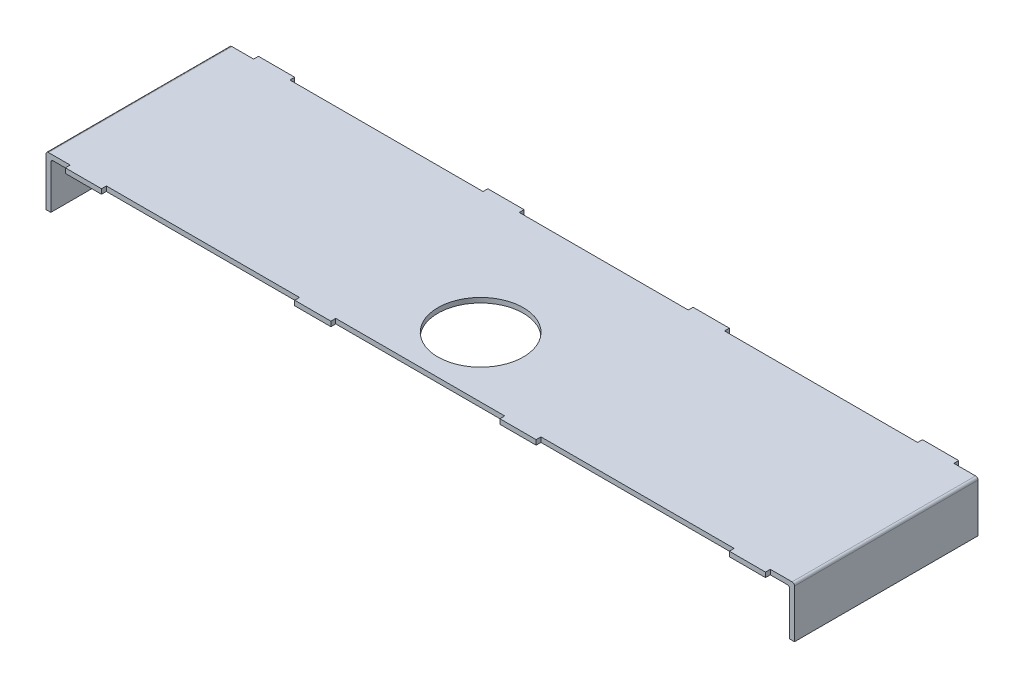
SolidWorks part; units mm, degrees
material "Hexcel AS4C (3000 丝)"
ref_plane "前视基准面" through (0, 0, 0) normal (0, 0, 1) x (1, 0, 0)
ref_plane "上视基准面" through (0, 0, 0) normal (0, 1, 0) x (1, 0, 0)
ref_plane "右视基准面" through (0, 0, 0) normal (1, 0, 0) x (0, 0, -1)
sketch "草图1" plane through (0, 0, 0) normal (0, 1, 0) x (1, 0, 0)
  line L0 (0, -25) -> (0, 25) construction
  line L1 (-155, -38) -> (-145, -38)
  line L2 (-155, -38) -> (-155, 38)
  line L3 (-155, 38) -> (-145, 38)
  line L4 (155, -38) -> (155, 38)
  line L5 (-155, -38) -> (155, 38) construction
  line L6 (-155, 38) -> (155, -38) construction
  line L7 (155, 0) -> (-155, 0) construction
  line L8 (-130, 38) -> (-50, 38)
  line L9 (-35, 38) -> (35, 38)
  line L10 (-145, 38) -> (-145, 40)
  line L11 (-145, 40) -> (-130, 40)
  line L12 (-130, 38) -> (-130, 40)
  line L13 (-145, 38) -> (-130, 40) construction
  line L14 (-145, 40) -> (-130, 38) construction
  line L15 (-50, 40) -> (-35, 40)
  line L16 (-50, 40) -> (-50, 38)
  line L17 (50, 40) -> (50, 38)
  line L18 (-35, 40) -> (-35, 38)
  line L19 (-50, 40) -> (-35, 38) construction
  line L20 (-50, 38) -> (-35, 40) construction
  line L21 (35, 40) -> (35, 38)
  line L22 (50, 40) -> (35, 40)
  line L23 (130, 38) -> (130, 40)
  line L24 (145, 38) -> (145, 40)
  line L25 (145, 40) -> (130, 40)
  line L26 (50, 38) -> (130, 38)
  line L27 (145, 38) -> (155, 38)
  line L28 (-130, -38) -> (-130, -40)
  line L29 (-145, -38) -> (-145, -40)
  line L30 (-145, -40) -> (-130, -40)
  line L31 (-50, -40) -> (-50, -38)
  line L32 (-35, -40) -> (-35, -38)
  line L33 (-50, -40) -> (-35, -40)
  line L34 (130, -38) -> (130, -40)
  line L35 (145, -38) -> (145, -40)
  line L36 (145, -40) -> (130, -40)
  line L37 (35, -40) -> (35, -38)
  line L38 (50, -40) -> (35, -40)
  line L39 (50, -40) -> (50, -38)
  line L40 (-130, -38) -> (-50, -38)
  line L41 (-35, -38) -> (35, -38)
  line L42 (50, -38) -> (130, -38)
  line L43 (145, -38) -> (155, -38)
  circle A0 centre (0, -13) radius 17.7
  point P0 (0, 0)
  point P6 (-137.5, 39)
  point P9 (0, 0)
  point P12 (0, 0)
  point P19 (-42.5, 39)
  dimension "D6" = 35.4
  dimension "D1" = 310
  dimension "D2" = 76
  dimension "D3" = 15
  dimension "D4" = 2
  dimension "D5" = 17.5
  dimension "D7" = 35
  dimension "D8" = 15
  dimension "D9" = 2
  dimension "D10" = 25
extrude "凸台-拉伸1" add sketch "草图1" along normal blind 2
sketch "草图2" plane through (0, 0, 0) normal (0, -1, 0) x (1, 0, 0)
  line L0 (155, 38) -> (155, -38) construction
  line L1 (155, -38) -> (153, -38)
  line L2 (155, -38) -> (155, 38)
  line L3 (155, 38) -> (153, 38)
  line L4 (153, -38) -> (153, 38)
  line L5 (155, -38) -> (205, -38) construction
  line L6 (145, 38) -> (155, 38) construction
  dimension "D1" = 2
extrude "凸台-拉伸2" add sketch "草图2" along normal blind 19
mirror "镜向1" about plane through (0, 0, 0) normal (1, 0, 0) of "凸台-拉伸2"
fillet "圆角1" radius 1 4 edges at (155, 2, 0) (153, 0, 0) (-153, 0, 0) (-155, 2, 0)
